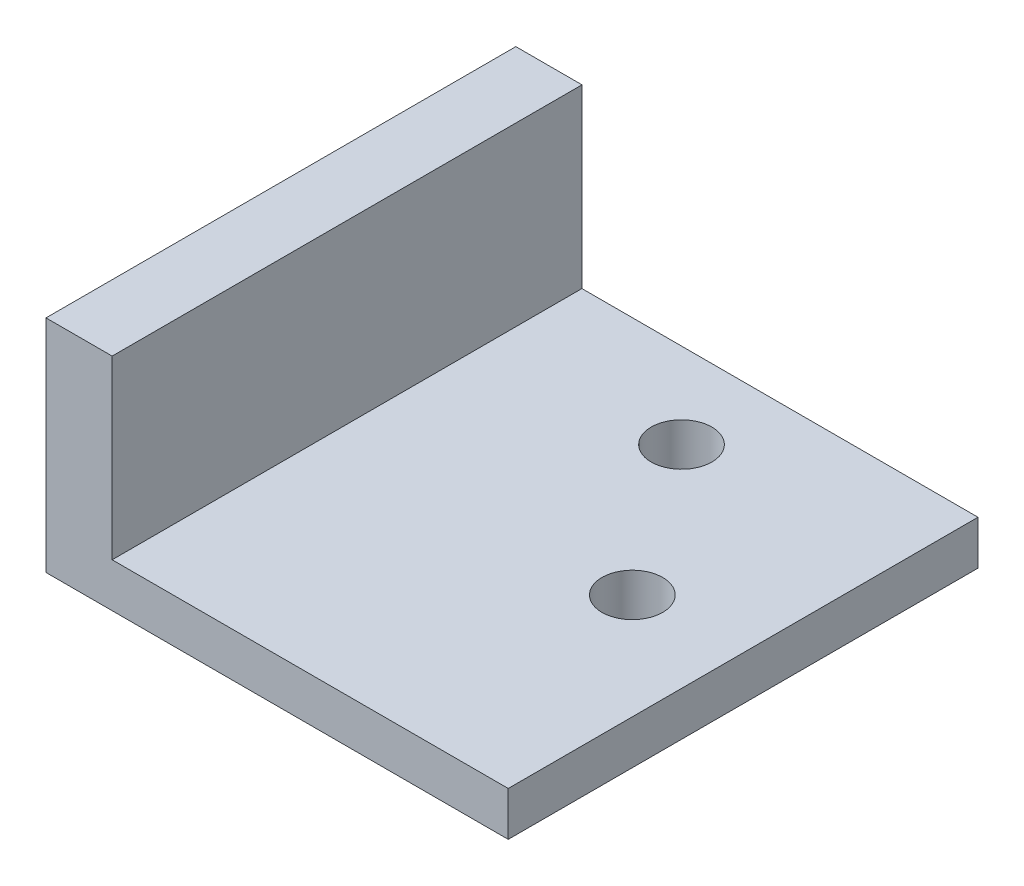
SolidWorks part; units mm, degrees
ref_plane "Front Plane" through (0, 0, 0) normal (0, 0, 1) x (1, 0, 0)
ref_plane "Top Plane" through (0, 0, 0) normal (0, 1, 0) x (1, 0, 0)
ref_plane "Right Plane" through (0, 0, 0) normal (1, 0, 0) x (0, 0, -1)
sketch "Sketch1" plane through (0, 0, 0) normal (0, 1, 0) x (1, 0, 0)
  line L1 (6.9799, 15.9817) -> (-6.9799, 15.9817)
  line L2 (6.9799, 15.9817) -> (6.9799, -5.3205)
  line L3 (6.9799, -5.3205) -> (-6.9799, -5.3205)
  line L16 (-6.9799, -5.3205) -> (-6.9799, 15.9817)
  circle A0 centre (-2.597, 12.1152) radius 1.375
  circle A1 centre (2.1933, 5.0936) radius 1.375
  point P0 (0, 0)
  dimension "D2" = 2.75
  dimension "D3" = 2.75
  dimension "D1" = 8.5
extrude "Boss-Extrude1" add sketch "Sketch1" along normal blind 2
sketch "Sketch2" plane through (0, 0, 0) normal (0, 1, 0) x (1, 0, 0)
  line L1 (-6.9799, 15.9817) -> (-10.9799, 15.9817)
  line L2 (-6.9799, 15.9817) -> (-6.9799, -5.3205)
  line L3 (-6.9799, -5.3205) -> (-10.9799, -5.3205)
  line L4 (-10.9799, 15.9817) -> (-10.9799, -5.3205)
  dimension "D1" = 4
extrude "Boss-Extrude2" add sketch "Sketch2" along normal blind 2
sketch "Sketch3" plane through (0, 0, 0) normal (0, 1, 0) x (1, 0, 0)
  line L0 (-10.9799, 15.9817) -> (-10.9799, -5.3205) construction
  line L5 (-10.9799, -5.3205) -> (-13.9799, -5.3205)
  line L6 (-10.9799, -5.3205) -> (-10.9799, 15.9846)
  line L7 (-10.9799, 15.9846) -> (-13.9799, 15.9846)
  line L8 (-13.9799, -5.3205) -> (-13.9799, 15.9846)
  point P6 (0, 0)
  dimension "D1" = 3
extrude "Boss-Extrude3" add sketch "Sketch3" along normal blind 10
